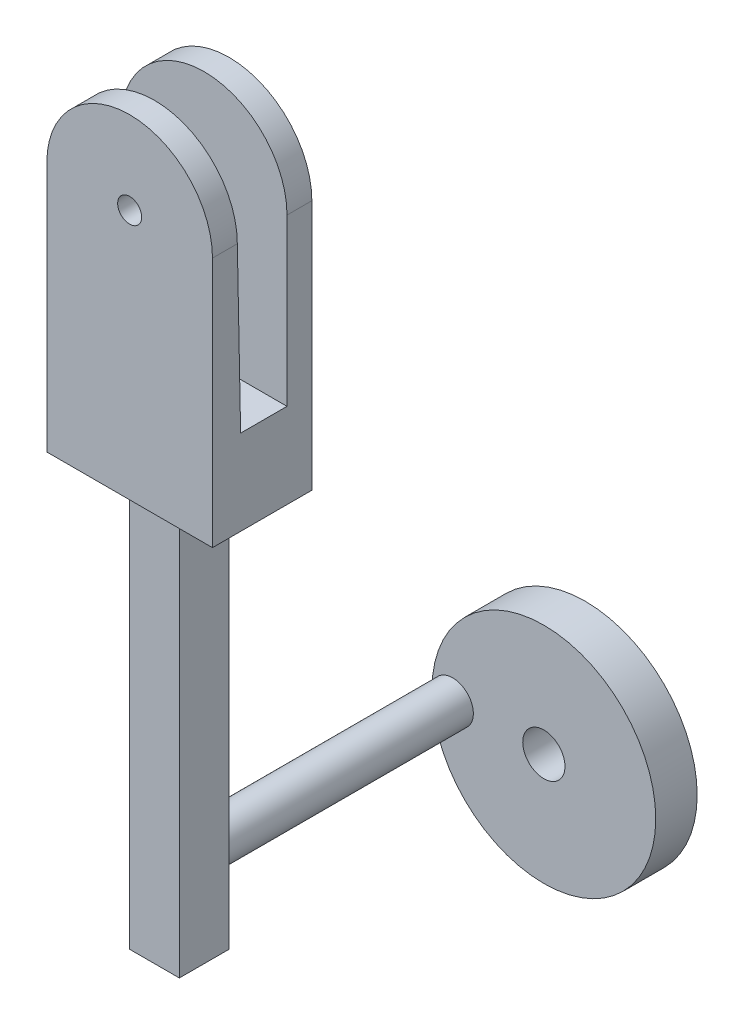
SolidWorks part; units mm, degrees
ref_plane "前基準面" through (0, 0, 0) normal (0, 0, 1) x (1, 0, 0)
ref_plane "上基準面" through (0, 0, 0) normal (0, 1, 0) x (1, 0, 0)
ref_plane "右基準面" through (0, 0, 0) normal (1, 0, 0) x (0, 0, -1)
sketch "草圖1" plane through (0, 0, 0) normal (0, 0, 1) x (1, 0, 0)
  line L0 (0, 0) -> (0, -11.05)
  line L1 (-10, 0) -> (-10, -30.2764)
  line L3 (10, -30.2764) -> (10, 0)
  line L4 (-10, -30.2764) -> (10, -30.2764)
  circle A1 centre (0, 0) radius 1.45
  arc A2 (10, 0) -> (-10, 0) centre (0, 0) ccw
  dimension "D1" = 11.05
  dimension "D2" = 2.9
  dimension "D3" = 20
extrude "填料-伸長1" add sketch "草圖1" along normal blind 12
sketch "草圖2" plane through (10, 0, 0) normal (1, 0, 0) x (0, 0, -1)
  line L0 (-12, 0) -> (-9.1, 0)
  line L1 (-12, 0) -> (0, 0) construction
  line L2 (-12, 10) -> (-12, 0) construction
  line L3 (0, 0) -> (-2.9, 0)
  line L4 (-6, 0) -> (-3, 0)
  line L5 (-6, 0) -> (-9, 0)
  line L6 (-9, 0) -> (-9, 15.7808)
  line L7 (-9, 15.7808) -> (-3, 15.7808)
  line L8 (-3, 15.7808) -> (-3, 0)
  line L9 (-3, 0) -> (-3, -20)
  line L10 (-9, 0) -> (-8.6005, -20)
  line L11 (-8.6005, -20) -> (-3, -20)
  line M8 (0, 0) -> (-12, 0)
  dimension "D1" = 2.9
  dimension "D2" = 2.9
  dimension "D3" = 3
  dimension "D4" = 3
  dimension "D5" = 20
extrude "除料-伸長1" cut sketch "草圖2" against normal through all contours L8 L7 L6 M8 | L10 L11 L9 M8
sketch "草圖3" plane through (0, -30.2764, 0) normal (0, -1, 0) x (1, 0, 0)
  line L0 (10, 6) -> (-10, 6)
  line L1 (10, 12) -> (10, 0) construction
  line L2 (-10, 12) -> (-10, 0) construction
  line L4 (3, 9) -> (-3, 9)
  line L5 (3, 9) -> (3, 3)
  line L6 (3, 3) -> (-3, 3)
  line L7 (-3, 9) -> (-3, 3)
  line L8 (3, 9) -> (-3, 3) construction
  line L9 (3, 3) -> (-3, 9) construction
  circle A0 centre (0, 6) radius 3.45
  dimension "D1" = 6.9
  dimension "D2" = 6
  dimension "D3" = 6
extrude "填料-伸長5" add sketch "草圖3" along normal blind 50 contours L5 L6 L7 L4
sketch "草圖8" plane through (0, 0, 3) normal (0, 0, -1) x (-1, 0, 0)
  line L0 (-3, -70.882) -> (3, -70.882)
  line L1 (-3, -80.2764) -> (-3, -30.2764) construction
  line L2 (3, -80.2764) -> (3, -30.2764) construction
  circle A0 centre (0, -70.882) radius 2.5
  dimension "D1" = 5
extrude "填料-伸長6" add sketch "草圖8" along normal blind 30 contours L0 A0 | L0 A0
sketch "草圖9" plane through (0, 0, -27) normal (0, 0, -1) x (-1, 0, 0)
  line L0 (2.5, -70.882) -> (-19.2996, -70.882)
  circle A0 centre (0, -70.882) radius 2.5 construction
  circle A1 centre (-11.011, -70.882) radius 13.511
extrude "填料-伸長10" add sketch "草圖9" along normal blind 5
sketch "草圖10" plane through (0, 0, -32) normal (0, 0, -1) x (-1, 0, 0)
  circle A0 centre (-11.011, -70.882) radius 2.55
  dimension "D1" = 5.1
extrude "除料-伸長5" cut sketch "草圖10" against normal through all
